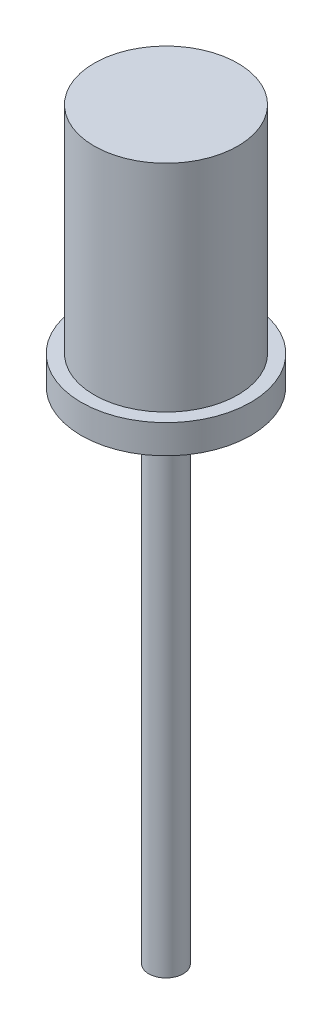
SolidWorks part; units mm, degrees
ref_plane "Front Plane" through (0, 0, 0) normal (0, 0, 1) x (1, 0, 0)
ref_plane "Top Plane" through (0, 0, 0) normal (0, 1, 0) x (1, 0, 0)
ref_plane "Right Plane" through (0, 0, 0) normal (1, 0, 0) x (0, 0, -1)
sketch "Sketch1" plane through (0, 0, 0) normal (0, 1, 0) x (1, 0, 0)
  circle A0 centre (0, 0) radius 2.95
  dimension "D1" = 5.9
extrude "Boss-Extrude1" add sketch "Sketch1" along normal blind 1
sketch "Sketch2" plane through (0, 1, 0) normal (0, 1, 0) x (1, 0, 0)
  circle A0 centre (0, 0) radius 2.5
  dimension "D1" = 5
extrude "Boss-Extrude2" add sketch "Sketch2" along normal blind 7.5
sketch "Sketch3" plane through (0, 0, 0) normal (0, -1, 0) x (1, 0, 0)
  circle A0 centre (0, 0) radius 0.6
  dimension "D1" = 1.2
extrude "Boss-Extrude3" add sketch "Sketch3" along normal blind 17.4
